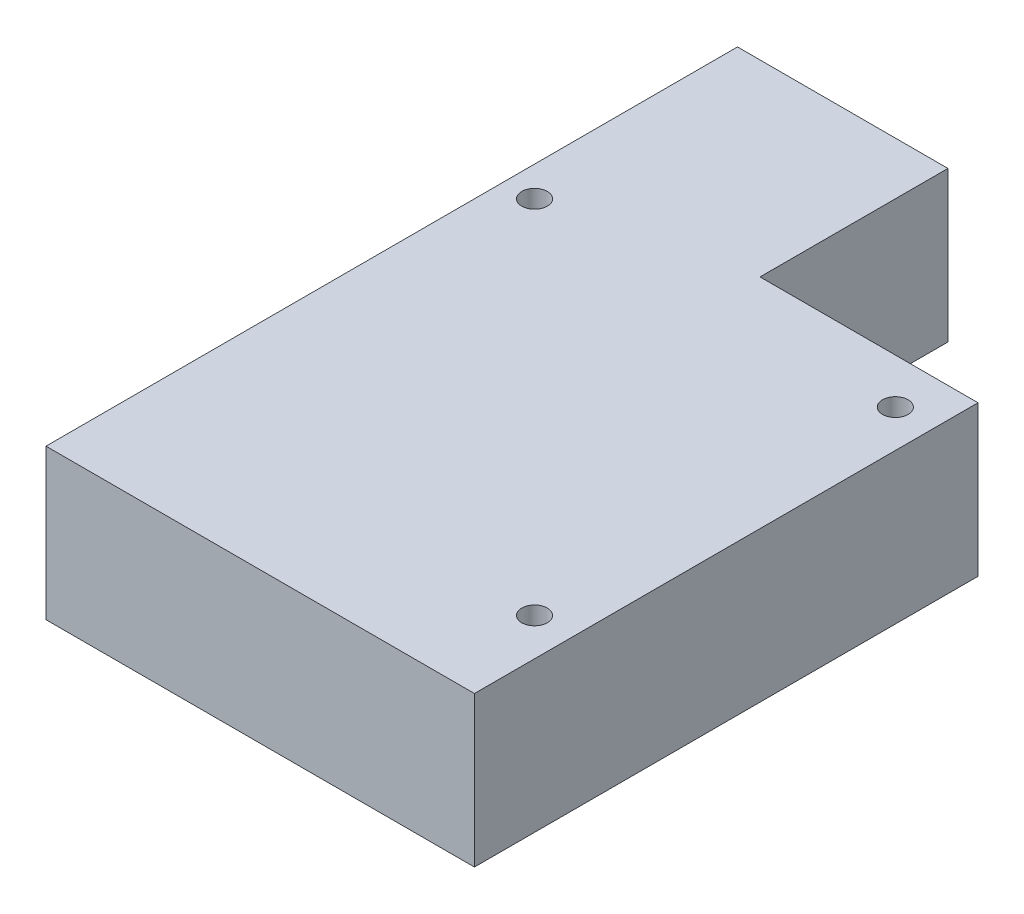
SolidWorks part; units mm, degrees
ref_plane "Front Plane" through (0, 0, 0) normal (0, 0, 1) x (1, 0, 0)
ref_plane "Top Plane" through (0, 0, 0) normal (0, 1, 0) x (1, 0, 0)
ref_plane "Right Plane" through (0, 0, 0) normal (1, 0, 0) x (0, 0, -1)
sketch "Sketch1" plane through (0, 0, 0) normal (0, 1, 0) x (1, 0, 0)
  line L1 (-28.5, -33.5) -> (28.5, -33.5)
  line L2 (-28.5, -33.5) -> (-28.5, 33.5)
  line L3 (-28.5, 33.5) -> (28.5, 33.5)
  line L4 (28.5, -33.5) -> (28.5, 33.5)
  line L5 (-28.5, -33.5) -> (28.5, 33.5) construction
  line L6 (-28.5, 33.5) -> (28.5, -33.5) construction
  point P0 (0, 0)
  dimension "D1" = 67
  dimension "D2" = 57
extrude "Boss-Extrude1" add sketch "Sketch1" along normal blind 20
sketch "Sketch2" plane through (0, 20, 0) normal (0, 1, 0) x (1, 0, 0)
  line L0 (-28.5, 33.5) -> (-28.5, -33.5) construction
  line L1 (-28.5, -33.5) -> (28.5, -33.5) construction
  circle A0 centre (-24.5, 27.5) radius 1.7
  circle A1 centre (23.5, 27.5) radius 1.7
  circle A2 centre (23.5, -20.5) radius 1.7
  point P6 (0, 0)
  point P7 (0, 0)
  dimension "D1" = 3.4
  dimension "D4" = 48
  dimension "D2" = 4
  dimension "D3" = 13
  dimension "D5" = 48
extrude "Cut-Extrude1" cut sketch "Sketch2" against normal blind 20
sketch "Sketch3" plane through (0, 0, -33.5) normal (0, 0, -1) x (-1, 0, 0)
  line L0 (-28.5, 0) -> (28.5, 0) construction
  line L1 (28.5, 20) -> (0.5, 20)
  line L2 (28.5, 20) -> (28.5, 0)
  line L3 (28.5, 0) -> (0.5, 0)
  line L4 (0.5, 20) -> (0.5, 0)
  dimension "D1" = 28
extrude "Boss-Extrude2" add sketch "Sketch3" along normal blind 25
